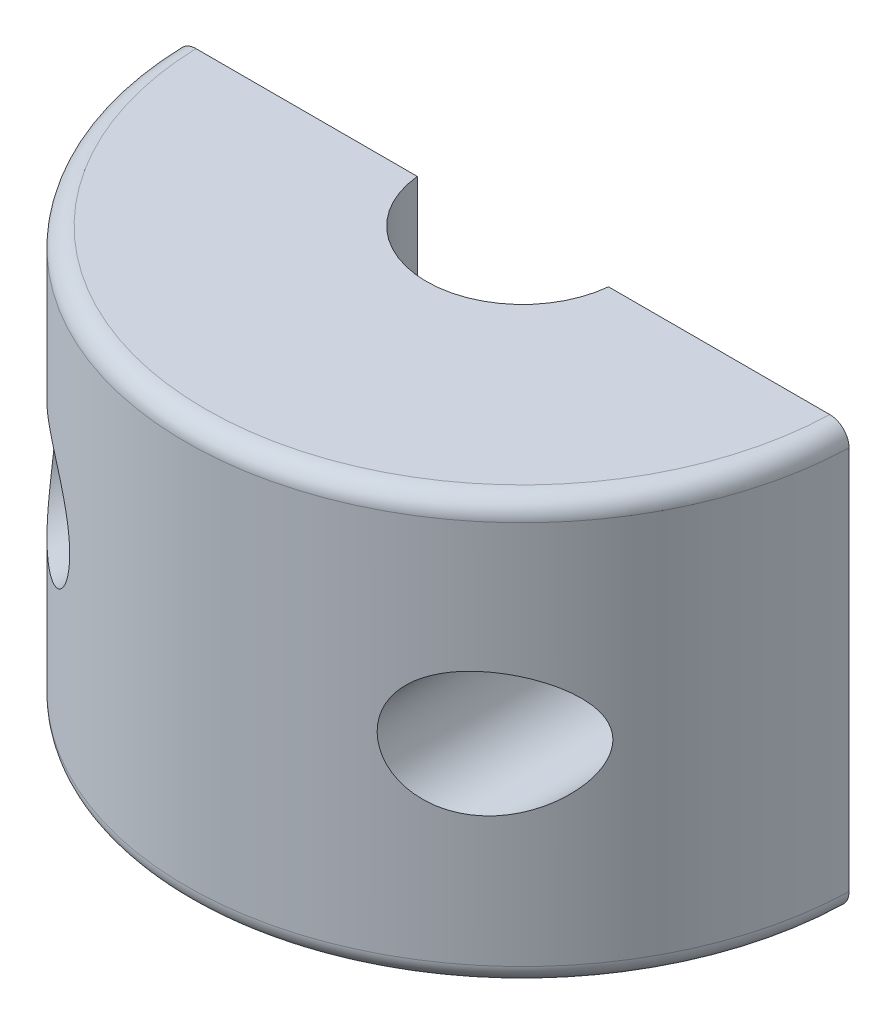
SolidWorks part; units mm, degrees
ref_plane "Front Plane" through (0, 0, 0) normal (0, 0, 1) x (1, 0, 0)
ref_plane "Top Plane" through (0, 0, 0) normal (0, 1, 0) x (1, 0, 0)
ref_plane "Right Plane" through (0, 0, 0) normal (1, 0, 0) x (0, 0, -1)
sketch "Sketch2" plane through (0, 0, 0) normal (0, 1, 0) x (1, 0, 0)
  line L0 (5, 0) -> (17.5, 0)
  line L1 (-5, 0) -> (-17.5, 0)
  arc A0 (-5, 0) -> (5, 0) centre (0, 0) ccw
  arc A1 (-17.5, 0) -> (17.5, 0) centre (0, 0) ccw
  dimension "D1" = 0
  dimension "D2" = 5
  dimension "D3" = 17.5
  dimension "D4" = 0
extrude "Boss-Extrude1" add sketch "Sketch2" along normal blind 22
sketch "Sketch3" plane through (0, 0, 0) normal (0, 0, -1) x (-1, 0, 0)
  line L0 (11.25, 22) -> (11.25, 0) construction
  line L1 (5, 22) -> (17.5, 22) construction
  line L2 (5, 0) -> (17.5, 0) construction
  line L3 (-11.25, 0) -> (-11.25, 22) construction
  line L4 (-17.5, 0) -> (-5, 0) construction
  line L5 (-17.5, 22) -> (-5, 22) construction
  circle A0 centre (11.25, 11) radius 1.75
  circle A1 centre (-11.25, 11) radius 1.75
  dimension "D1" = 3.5
extrude "Cut-Extrude1" cut sketch "Sketch3" against normal blind 22
ref_plane "Plane1" through (0, 0, 4.5) normal (0, 0, -1) x (-1, 0, 0)
sketch "Sketch4" plane through (0, 0, 4.5) normal (0, 0, -1) x (-1, 0, 0)
  circle A0 centre (-11.25, 11) radius 3.25
  circle A1 centre (11.25, 11) radius 3.25
  dimension "D1" = 6.5
extrude "Cut-Extrude2" cut sketch "Sketch4" against normal blind 22
fillet "Fillet1" radius 1 2 edges at (0, 0, 17.5) (0, 22, 17.5)
sketch "Sketch5" plane through (0, 22, 0) normal (0, 1, 0) x (1, 0, 0)
  line L0 (16.5, 0) -> (5, 0) construction
  line L1 (-18.4386, 0) -> (18.1449, 0)
  line L2 (-18.4386, 0) -> (-18.4386, -0.5)
  line L3 (-18.4386, -0.5) -> (18.1449, -0.5)
  line L4 (18.1449, 0) -> (18.1449, -0.5)
  dimension "D1" = 0.5
extrude "Cut-Extrude3" cut sketch "Sketch5" against normal blind 39
